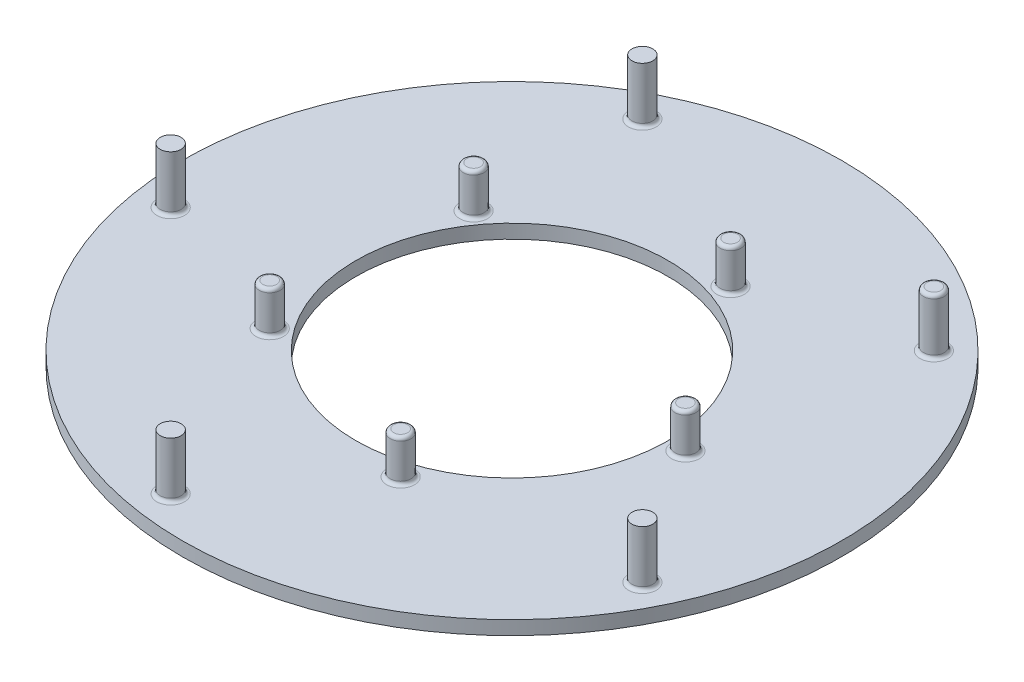
SolidWorks part; units mm, degrees
ref_plane "Front Plane" through (0, 0, 0) normal (0, 0, 1) x (1, 0, 0)
ref_plane "Top Plane" through (0, 0, 0) normal (0, 1, 0) x (1, 0, 0)
ref_plane "Right Plane" through (0, 0, 0) normal (1, 0, 0) x (0, 0, -1)
sketch "Sketch1" plane through (0, 0, 0) normal (0, 1, 0) x (1, 0, 0)
  circle A0 centre (0, 0) radius 22.5
  circle A1 centre (0, 0) radius 47.5
  dimension "D1" = 45
  dimension "D2" = 95
extrude "Boss-Extrude1" add sketch "Sketch1" along normal blind 2
sketch "Sketch2" plane through (0, 2, 0) normal (0, 1, 0) x (1, 0, 0)
  line L0 (-67.5192, 0) -> (70.5599, 0) construction
  line L1 (0, 58.8306) -> (0, -59.2797) construction
  line L2 (0, 0) -> (30.4056, 30.4056) construction
  circle A0 centre (25, 0) radius 1.5
  circle A1 centre (30.4056, 30.4056) radius 1.5
  circle A2 centre (0, 0) radius 25 construction
  circle A3 centre (0, 0) radius 43 construction
  dimension "D1" = 3
  dimension "D2" = 3
  dimension "D3" = 50
  dimension "D4" = 86
  dimension "D5" = 45
extrude "Boss-Extrude2" add sketch "Sketch2" along normal blind 6
fillet "Fillet1" radius 0.5 3 edges at (30.4056, 2, -28.9056) (25, 2, 1.5) (25, 8, 1.5)
sketch "Sketch3" plane through (0, 8, 0) normal (0, 1, 0) x (1, 0, 0)
  circle A0 centre (30.4056, 30.4056) radius 1.5 construction
  circle A1 centre (30.4056, 30.4056) radius 1.5
extrude "Boss-Extrude3" add sketch "Sketch3" along normal blind 2
fillet "Fillet2" radius 0.5 1 edges at (30.4056, 10, -28.9056)
pattern_circular "CirPattern1" count 5 over 360 about axis through (0, 0, 0) along (0, 1, 0) of "Boss-Extrude2", "Fillet1", "Boss-Extrude3"
